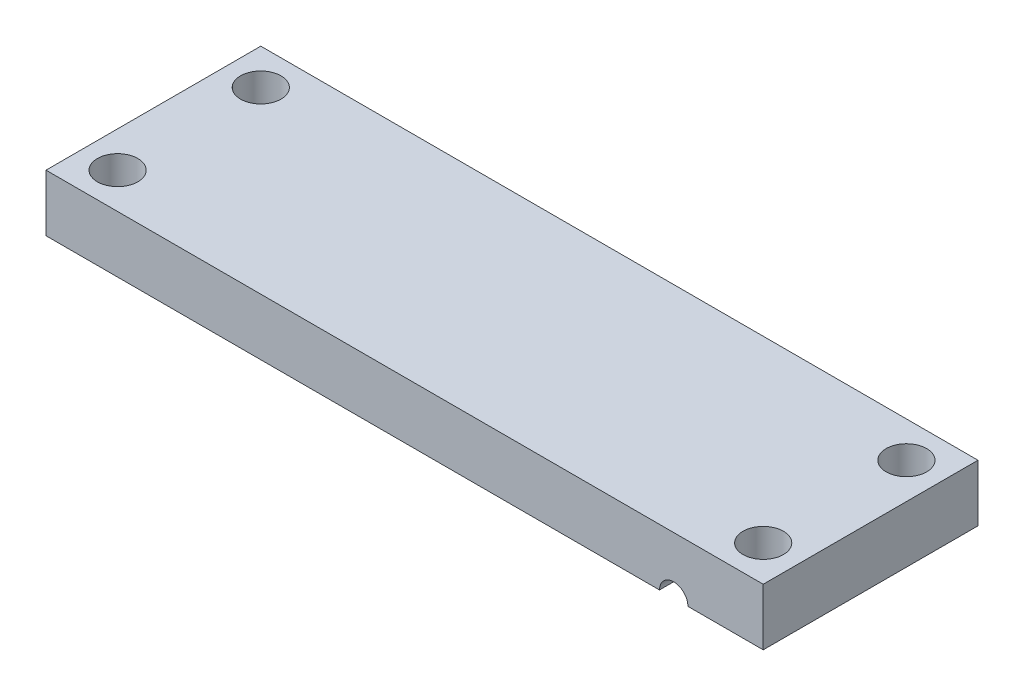
SolidWorks part; units mm, degrees
ref_plane "Front Plane" through (0, 0, 0) normal (0, 0, 1) x (1, 0, 0)
ref_plane "Top Plane" through (0, 0, 0) normal (0, 1, 0) x (1, 0, 0)
ref_plane "Right Plane" through (0, 0, 0) normal (1, 0, 0) x (0, 0, -1)
sketch "Sketch1" plane through (0, 0, 0) normal (0, 1, 0) x (1, 0, 0)
  line L0 (2, -2) -> (38.07, -2)
  line L1 (2, -2) -> (2, -10)
  line L2 (2, -10) -> (38.07, -10)
  line L3 (38.07, -2) -> (38.07, -10)
  line L4 (0, 0) -> (40.07, 0)
  line L5 (0, 0) -> (0, -12)
  line L6 (0, -12) -> (40.07, -12)
  line L7 (40.07, 0) -> (40.07, -12)
  circle A0 centre (2, -2) radius 1.1303
  circle A1 centre (38.07, -2) radius 1.1303
  circle A2 centre (38.07, -10) radius 1.1303
  circle A3 centre (2, -10) radius 1.1303
  circle A4 centre (2, -2) radius 1.7907 construction
  circle A5 centre (2, -10) radius 1.7907 construction
  circle A6 centre (38.07, -10) radius 1.7907 construction
  circle A7 centre (38.07, -2) radius 1.7907 construction
  dimension "D3" = 2.2606
  dimension "D1" = 3.5814
  dimension "D2" = 36.07
  dimension "D4" = 8
  dimension "D5" = 2
  dimension "D6" = 2
  dimension "D7" = 2
  dimension "D8" = 2
extrude "Boss-Extrude1" add sketch "Sketch1" along normal blind 3.175 contours L7 L4 L5 L6 A3 L1 A0 L0 A1 L3 A2 L2 | A3 L2 A2 L3 A1 L0 A0 L1
sketch "Sketch2" plane through (0, 0, 0) normal (0, 1, 0) x (1, 0, 0)
  line L0 (8.175, -8.4) -> (8.175, -4.9)
  line L1 (0, 0) -> (40.07, 0) construction
  line L2 (11.35, -4.9) -> (11.35, -8.4)
  line L3 (14.525, -8.4) -> (14.525, -4.9)
  line L4 (17.0723, -3.3125) -> (16.1125, -3.3125)
  line L6 (5, -8.4) -> (5, 0)
  line L7 (20.035, 0) -> (20.035, -12) construction
  line L8 (0, -12) -> (40.07, -12) construction
  line L9 (0, -6) -> (40.07, -6) construction
  line L10 (0, 0) -> (0, -12) construction
  line L11 (40.07, 0) -> (40.07, -12) construction
  line L13 (17.0723, -3.3125) -> (22.9977, -8.6875)
  line L14 (2, -2) -> (2, -10) construction
  line L15 (3.1394, -6.4821) -> (5, -8.4)
  line L16 (38.07, -10) -> (38.07, -2) construction
  line L18 (35.07, -3.6) -> (35.07, -12)
  line L19 (31.895, -3.6) -> (31.895, -7.1)
  line L20 (28.72, -7.1) -> (28.72, -3.6)
  line L21 (25.545, -3.6) -> (25.545, -7.1)
  line L23 (22.9977, -8.6875) -> (23.9575, -8.6875)
  line L24 (38.07, -6) -> (35.07, -3.6)
  circle A0 centre (20.035, -6) radius 4
  arc A1 (5, -8.4) -> (8.175, -8.4) centre (6.5875, -8.4) ccw
  arc A2 (11.35, -4.9) -> (8.175, -4.9) centre (9.7625, -4.9) ccw
  arc A5 (11.35, -8.4) -> (14.525, -8.4) centre (12.9375, -8.4) ccw
  arc A7 (16.1125, -3.3125) -> (14.525, -4.9) centre (16.1125, -4.9) ccw
  arc A10 (28.72, -3.6) -> (25.545, -3.6) centre (27.1325, -3.6) ccw
  arc A13 (3.1394, -6.4821) -> (2, -6) centre (2, -7.5875) ccw
  arc A14 (35.07, -3.6) -> (31.895, -3.6) centre (33.4825, -3.6) ccw
  arc A15 (28.72, -7.1) -> (31.895, -7.1) centre (30.3075, -7.1) ccw
  arc A16 (23.9575, -8.6875) -> (25.545, -7.1) centre (23.9575, -7.1) ccw
  point P5 (20.035, 0)
  point P11 (2, -6)
  point P20 (20.035, -2)
  point P38 (0, 0)
  dimension "D3" = 3.175
  dimension "D1" = 8
  dimension "D4" = 3.5
  dimension "D5" = 3.6
  dimension "D2" = 5
  dimension "D6" = 5
sketch "Sketch3" plane through (0, 0, 0) normal (0, 0, -1) x (-1, 0, 0)
  line L0 (0, 0) -> (-40.07, 0) construction
  circle A0 centre (-5, 0) radius 0.7938
  dimension "D1" = 1.5875
sweep "Cut-Sweep5" cut profiles "Sketch3" path "Sketch2"
sketch "Sketch5" plane through (0, 0, 12) normal (0, 0, 1) x (1, 0, 0)
  circle A0 centre (35.07, 0) radius 0.7937
  arc A2 (35.8638, 0) -> (34.2763, 0) centre (35.07, 0) ccw construction
  point P2 (0, 0)
  point P3 (48.1608, -7.6412)
  point P7 (0, 0)
  dimension "D1" = 1.5875
sketch "Sketch6" plane through (0, 0, 0) normal (0, -1, 0) x (-1, 0, 0)
  line L1 (-38.07, -2) -> (-38.07, -10) construction
  line L3 (-35.07, -3.6) -> (-38.07, -6)
  line L5 (-35.07, -3.6) -> (-35.07, -12)
  line L6 (-34.2763, -3.6) -> (-35.8638, -3.6) construction
  line L7 (-35.8638, -12) -> (-34.2763, -12) construction
  line L9 (-5, 0) -> (-5, -8.4)
  line L10 (-4.2063, 0) -> (-5.7938, 0) construction
  line L11 (-4.2062, -8.4) -> (-5.7938, -8.4) construction
  line L12 (-5, -8.4) -> (-2, -6)
  circle A2 centre (-38.07, -10) radius 1.1303 construction
  point P5 (0, 0)
  point P6 (-2, -6)
  point P8 (-38.07, -10.5265)
  point P10 (0, 0)
  point P13 (-38.07, -6)
  point P14 (0, 0)
  point P34 (0, 0)
  point P35 (-38.07, -7.1793)
  point P36 (-38.07, -7.1793)
sweep "Cut-Sweep10" cut profiles "Sketch5" path "Sketch6"
sketch "Sketch8" plane through (0, 0, 0) normal (0, 0, -1) x (-1, 0, 0)
  line L0 (-3.1303, 0) -> (-0.8697, 0) construction
  circle A0 centre (-5, 0) radius 0.7938
  arc A1 (-4.2062, 0) -> (-5.7938, 0) centre (-5, 0) ccw construction
sketch "Sketch9" plane through (0, 0, 0) normal (0, -1, 0) x (1, 0, 0)
  line L0 (2, 10) -> (2, 2) construction
  line L1 (5, 0) -> (5, 8.4)
  line L2 (4.2062, 0) -> (5.7938, 0) construction
  line L3 (4.2062, 8.4) -> (5.7938, 8.4) construction
  line L4 (5, 8.4) -> (2, 6)
  circle A0 centre (2, 10) radius 1.1303 construction
  circle A1 centre (2, 2) radius 1.1303 construction
sweep "Cut-Sweep11" cut profiles "Sketch8" path "Sketch9"
equation "\"D7@Sketch1\"=\"D5@Sketch1\""
equation "\"D8@Sketch1\"=\"D5@Sketch1\""
equation "\"D6@Sketch1\"=\"D5@Sketch1\""
equation "\"D6@Sketch2\"=\"D2@Sketch2\""
